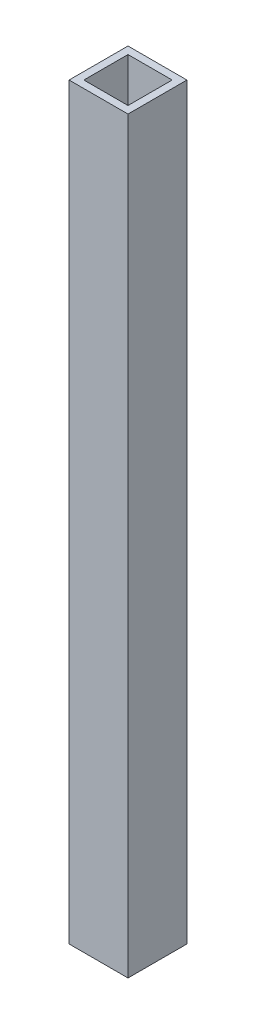
SolidWorks part; units mm, degrees
material "Thornel Mat VMA"
ref_plane "Front Plane" through (0, 0, 0) normal (0, 0, 1) x (1, 0, 0)
ref_plane "Top Plane" through (0, 0, 0) normal (0, 1, 0) x (1, 0, 0)
ref_plane "Right Plane" through (0, 0, 0) normal (1, 0, 0) x (0, 0, -1)
sketch "Sketch1" plane through (0, 0, 0) normal (0, 1, 0) x (1, 0, 0)
  line L1 (0, 0) -> (8.001, 0)
  line L2 (0, 0) -> (0, 8.001)
  line L3 (0, 8.001) -> (8.001, 8.001)
  line L4 (8.001, 0) -> (8.001, 8.001)
  dimension "D1" = 8.001
  dimension "D2" = 8.001
extrude "Boss-Extrude1" add sketch "Sketch1" along normal blind 101.6
sketch "Sketch2" plane through (0, 101.6, 0) normal (0, 1, 0) x (1, 0, 0)
  line L1 (1.0033, 6.9977) -> (6.9977, 6.9977)
  line L2 (1.0033, 6.9977) -> (1.0033, 1.0033)
  line L3 (1.0033, 1.0033) -> (6.9977, 1.0033)
  line L4 (6.9977, 6.9977) -> (6.9977, 1.0033)
  line L5 (8.001, 8.001) -> (0, 8.001) construction
  line L6 (0, 8.001) -> (0, 0) construction
  dimension "D1" = 5.9944
  dimension "D2" = 5.9944
  dimension "D3" = 1.0033
  dimension "D4" = 1.0033
extrude "Cut-Extrude1" cut sketch "Sketch2" against normal through all
ref_plane "Plane1" through (0, 0, -4.0005) normal (0, 0, 1) x (1, 0, 0)
ref_plane "Plane2" through (4.0005, 0, 0) normal (-1, 0, 0) x (0, 0, 1)
